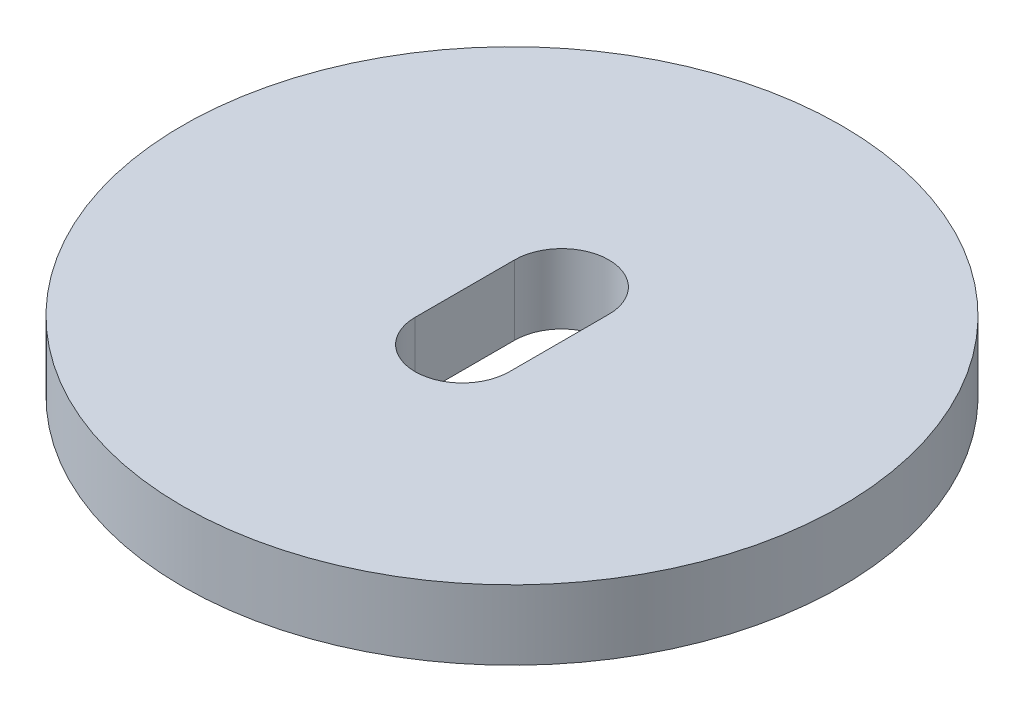
SolidWorks part; units mm, degrees
ref_plane "Front Plane" through (0, 0, 0) normal (0, 0, 1) x (1, 0, 0)
ref_plane "Top Plane" through (0, 0, 0) normal (0, 1, 0) x (1, 0, 0)
ref_plane "Right Plane" through (0, 0, 0) normal (1, 0, 0) x (0, 0, -1)
sketch "Sketch1" plane through (0, 0, 0) normal (0, 1, 0) x (1, 0, 0)
  line L0 (0, -2) -> (0, 2) construction
  line L1 (-1.895, -2) -> (-1.895, 2)
  line L2 (1.895, -2) -> (1.895, 2)
  circle A0 centre (0, 0) radius 13.25
  arc A1 (-1.895, -2) -> (1.895, -2) centre (0, -2) ccw
  arc A2 (1.895, 2) -> (-1.895, 2) centre (0, 2) ccw
  point P5 (0, 0)
  dimension "D1" = 26.5
  dimension "D3" = 4
  dimension "D2" = 3.79
extrude "Boss-Extrude1" add sketch "Sketch1" along normal blind 2.8
